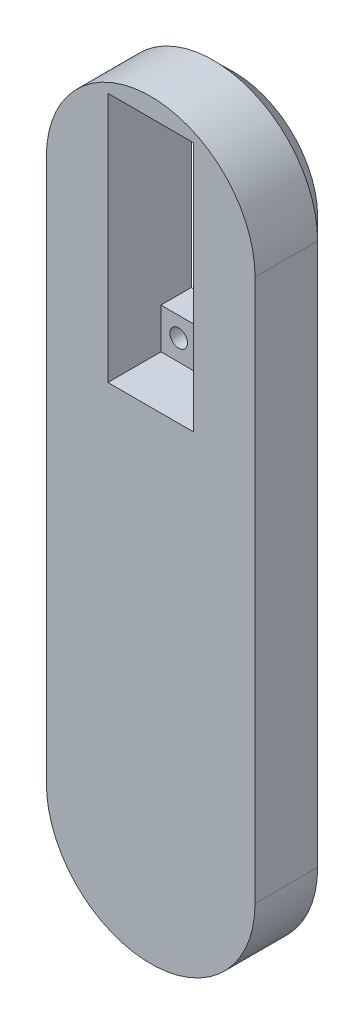
SolidWorks part; units mm, degrees
ref_plane "Front Plane" through (0, 0, 0) normal (0, 0, 1) x (1, 0, 0)
ref_plane "Top Plane" through (0, 0, 0) normal (0, 1, 0) x (1, 0, 0)
ref_plane "Right Plane" through (0, 0, 0) normal (1, 0, 0) x (0, 0, -1)
sketch "Sketch1" plane through (0, 0, 0) normal (0, 0, 1) x (1, 0, 0)
  line L0 (0, 0) -> (0, 147.804) construction
  line L2 (43.2, 51) -> (-43.2, 51) construction
  line L4 (0, 130) -> (0, 0) construction
  line L6 (25, 130) -> (25, 0)
  line L7 (-25, 130) -> (-25, 0)
  arc A1 (25, 130) -> (-25, 130) centre (0, 130) ccw
  arc A2 (-25, 0) -> (25, 0) centre (0, 0) ccw
  point P2 (-25, 131.7091)
  point P7 (0, 65)
  point P11 (0, 51)
  dimension "D1" = 130
  dimension "D3" = 50
extrude "Boss-Extrude1" add sketch "Sketch1" along normal mid plane 20
chamfer "Chamfer1" distance 5 angle 45 4 edges at (-25, 65, -10) (0, -25, -10) (25, 65, -10) (0, 155, -10)
sketch "Sketch3" plane through (0, 0, 0) normal (1, 0, 0) x (0, 0, -1)
  line L0 (-10, 120.5) -> (29.3, 120.5) construction
  line L1 (29.3, 101.5) -> (29.3, 139.5) construction
  line L2 (2.7, 140.79) -> (2.7, 150.5)
  line L3 (2.7, 150.5) -> (-10, 150.5)
  line L4 (-0.3, 147.5) -> (2.7, 147.5) construction
  line L5 (2.7, 140.79) -> (10, 140.79)
  line L7 (10, 140.79) -> (10, 120.5)
  line L8 (-10, 0) -> (-10, 130) construction
  line L9 (10, 120.5) -> (-10, 120.5)
  line L10 (10, 0) -> (10, 130) construction
  line L11 (-10, 120.5) -> (-10, 150.5)
  point P2 (-9.6221, 121.5)
  point P3 (10, 121.5)
  point P6 (29.3, 120.5)
  point P8 (-16, 121.5)
  point P12 (-16, 121.5)
  point P17 (-10, 121.5)
  dimension "D1" = 20.29
  dimension "D2" = 3
  dimension "D3" = 12.7
extrude "Cut-Extrude1" cut sketch "Sketch3" against normal mid plane 20.5
ref_axis "Axis1" through (-6, 145.5, -58.1458) along (0, 0, 1)
ref_plane "Plane1" through (-6, 0, 0) normal (1, 0, 0) x (0, 0, -1)
sketch "Sketch4" plane through (-6, 0, 0) normal (1, 0, 0) x (0, 0, -1)
  line L0 (58.1458, 145.5) -> (53.6458, 145.5) construction
  line L1 (2.7, 145.5) -> (12.7, 145.5)
  line L2 (2.7, 140.79) -> (2.7, 150.5) construction
  line L3 (2.7, 145.5) -> (2.7, 147.6)
  line L4 (2.7, 147.6) -> (8.7, 147.6)
  line L5 (8.7, 147.6) -> (8.7, 146.85)
  line L6 (8.7, 146.85) -> (12.7, 146.85)
  line L7 (12.7, 146.85) -> (12.7, 145.5)
  dimension "D1" = 10
  dimension "D2" = 2.1
  dimension "D3" = 1.35
  dimension "D4" = 6
revolve "Cut-Revolve1" cut sketch "Sketch4" angle 360 about axis through (-6, 145.5, -58.1458) along (0, 0, 1)
ref_plane "Plane2" through (0, 0, 0) normal (1, 0, 0) x (0, 0, -1)
mirror "Mirror1" about plane through (0, 0, 0) normal (1, 0, 0) of "Cut-Revolve1"
mirror "Mirror2" about plane through (-10.25, 120.5, -10) normal (0, -1, 0) of "Mirror1", "Cut-Extrude1", "Cut-Revolve1"
sketch "Sketch5" plane through (0, 0, -2.7) normal (0, 0, 1) x (1, 0, 0)
  line L0 (-10.25, 140.79) -> (10.25, 140.79) construction
  line L1 (-3.2, 140.79) -> (3.2, 140.79)
  line L2 (-3.2, 140.79) -> (-3.2, 147.5)
  line L3 (-3.2, 147.5) -> (3.2, 147.5)
  line L4 (3.2, 140.79) -> (3.2, 147.5)
  line L5 (4.3379, 147.5) -> (-4.3379, 147.5) construction
  line L7 (3.2, 147.5) -> (3.2, 142.5) construction
  line L8 (-3.2, 147.5) -> (-3.2, 142.5) construction
extrude "Cut-Extrude2" cut sketch "Sketch5" against normal blind 24
